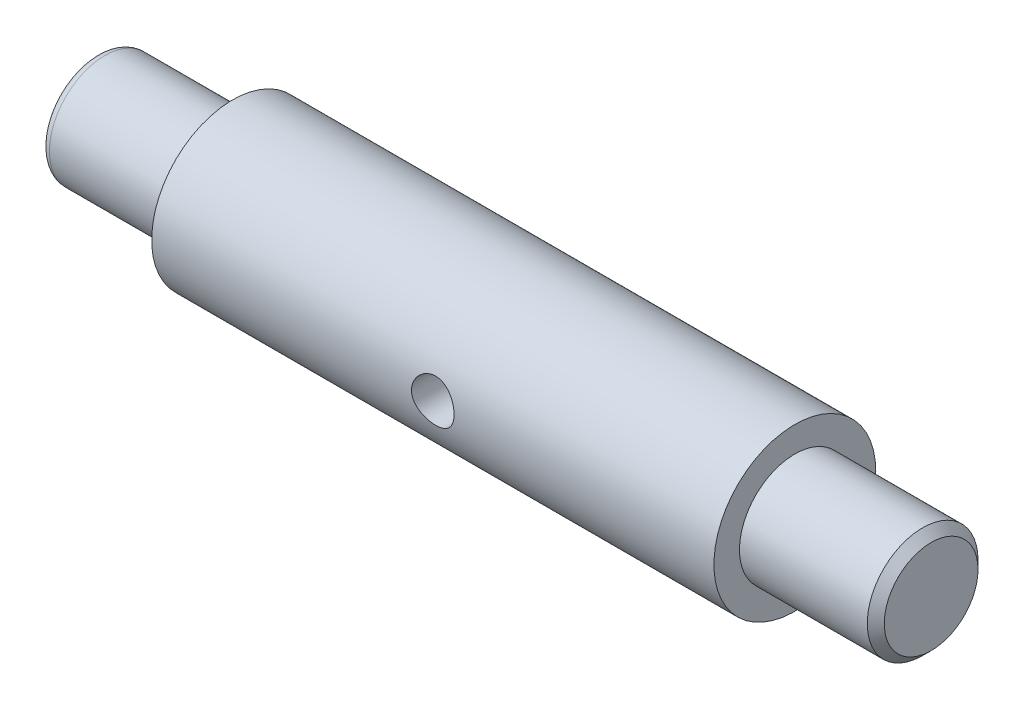
SolidWorks part; units mm, degrees
ref_plane "Front Plane" through (0, 0, 0) normal (0, 0, 1) x (1, 0, 0)
ref_plane "Top Plane" through (0, 0, 0) normal (0, 1, 0) x (1, 0, 0)
ref_plane "Right Plane" through (0, 0, 0) normal (1, 0, 0) x (0, 0, -1)
sketch "Sketch3" plane through (0, 0, 0) normal (0, 1, 0) x (1, 0, 0)
  line L0 (-49.546, 0) -> (60.3928, 0) construction
  line L2 (-33, 9.5) -> (33, 9.5)
  line L3 (-33, 9.5) -> (-33, 6.5)
  line L5 (33, 9.5) -> (33, 6.5)
  line L6 (-33, 9.5) -> (0, 0) construction
  line L7 (0, 0) -> (33, 9.5) construction
  line L8 (49, 6.5) -> (33, 6.5)
  line L9 (49, 6.5) -> (49, 0)
  line L12 (49, 6.5) -> (41, 0) construction
  line L13 (41, 0) -> (33, 6.5) construction
  line L14 (-48, 6.5) -> (-33, 6.5)
  line L15 (-49, 5.5) -> (-49, 3.625)
  line L18 (-49, 6.5) -> (-41, 0) construction
  line L19 (-41, 0) -> (-33, 6.5) construction
  line L21 (-48, 3) -> (-48.375, 3)
  line L25 (-48, 3) -> (-48, 0)
  line L26 (49, 0) -> (-48, 0)
  arc A0 (-48, 6.5) -> (-49, 5.5) centre (-48, 5.5) ccw
  arc A1 (-48.375, 3) -> (-49, 3.625) centre (-48.375, 3.625) cw
  point P3 (0, 0)
  point P8 (41, 0)
  point P13 (-41, 0)
  dimension "D1" = 1
  dimension "D2" = 0.625
revolve "Revolve1" add sketch "Sketch3" angle 360 about L26
chamfer "Chamfer1" distance 1 angle 45 1 edges at (49, 0, -6.5)
sketch "Sketch5" plane through (-48, 0, 0) normal (-1, 0, 0) x (0, 0, 1)
  circle A0 centre (0, 0) radius 3
  dimension "D1" = 6
extrude "Cut-Extrude1" cut sketch "Sketch5" against normal blind 60
sketch "Sketch7" plane through (0, 0, 0) normal (0, 0, 1) x (1, 0, 0)
  circle A0 centre (0, 0) radius 2.5
  dimension "D1" = 5
extrude "Cut-Extrude2" cut sketch "Sketch7" against normal mid plane 50
